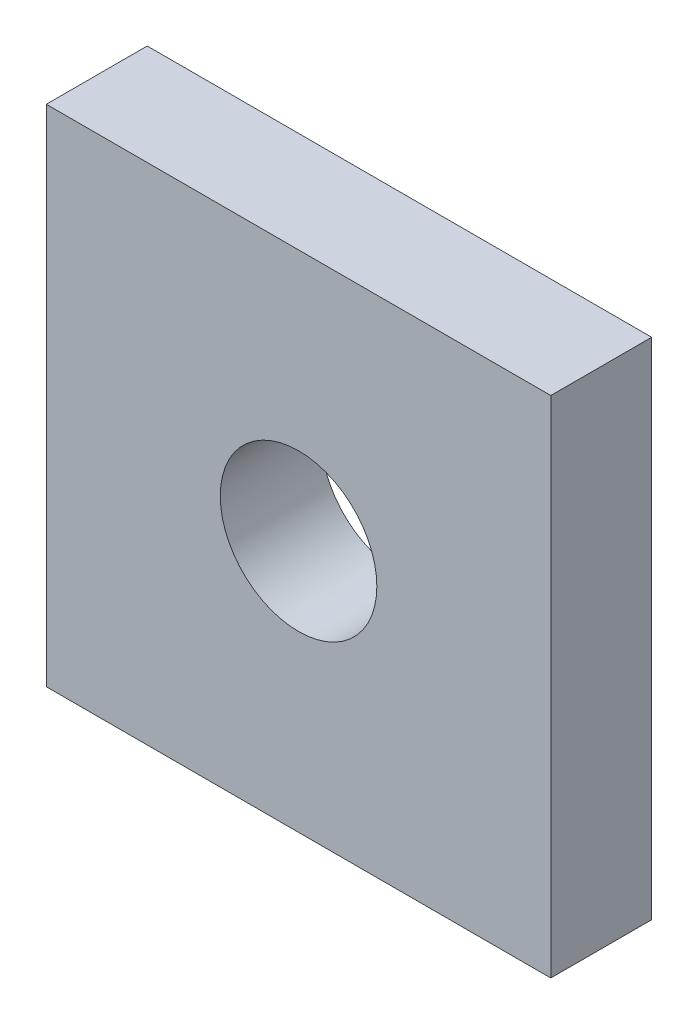
SolidWorks part; units mm, degrees
ref_plane "Front Plane" through (0, 0, 0) normal (0, 0, 1) x (1, 0, 0)
ref_plane "Top Plane" through (0, 0, 0) normal (0, 1, 0) x (1, 0, 0)
ref_plane "Right Plane" through (0, 0, 0) normal (1, 0, 0) x (0, 0, -1)
sketch "Sketch1" plane through (0, 0, 0) normal (0, 0, 1) x (1, 0, 0)
  line L1 (175, -175) -> (-175, -175)
  line L2 (175, -175) -> (175, 175)
  line L3 (175, 175) -> (-175, 175)
  line L4 (-175, -175) -> (-175, 175)
  line L5 (175, -175) -> (-175, 175) construction
  line L6 (175, 175) -> (-175, -175) construction
  point P0 (0, 0)
  dimension "D1" = 350
  dimension "D2" = 350
extrude "Boss-Extrude1" add sketch "Sketch1" along normal blind 70
sketch "Sketch2" plane through (0, 0, 70) normal (0, 0, 1) x (1, 0, 0)
  circle A0 centre (0, 0) radius 54.3152
extrude "Cut-Extrude1" cut sketch "Sketch2" against normal blind 70
